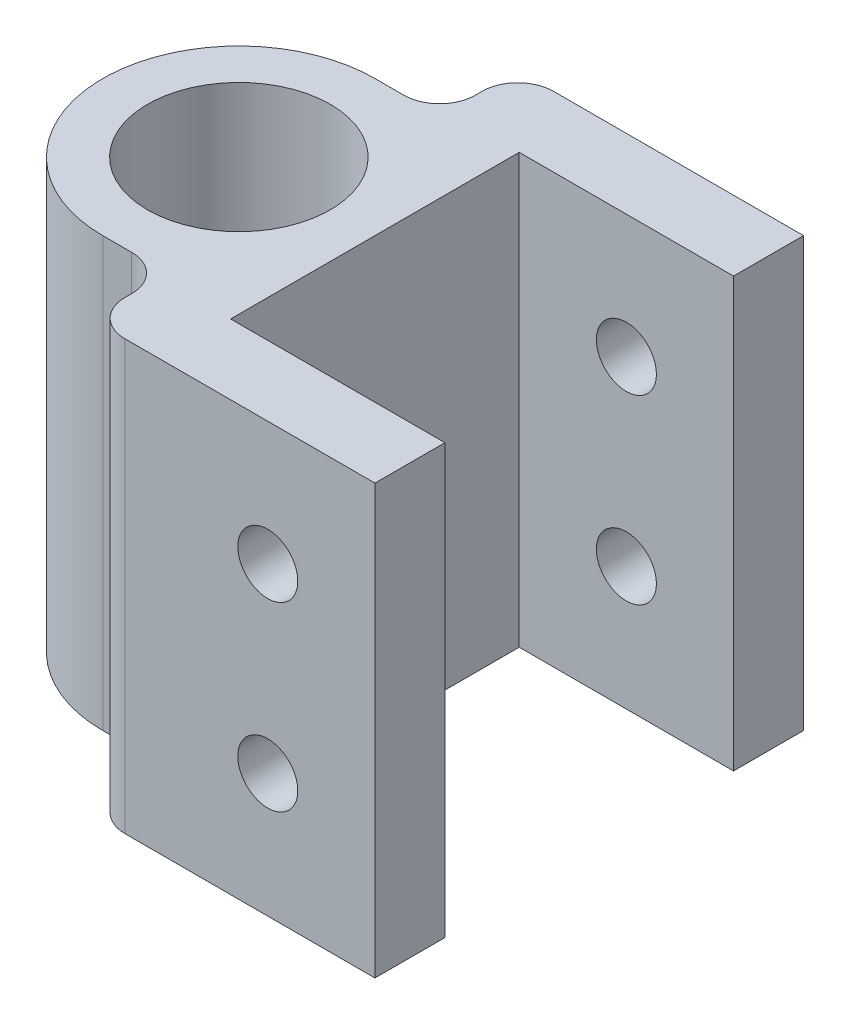
SolidWorks part; units mm, degrees
ref_plane "Front Plane" through (0, 0, 0) normal (0, 0, 1) x (1, 0, 0)
ref_plane "Top Plane" through (0, 0, 0) normal (0, 1, 0) x (1, 0, 0)
ref_plane "Right Plane" through (0, 0, 0) normal (1, 0, 0) x (0, 0, -1)
sketch "Sketch1" plane through (0, 0, 0) normal (0, 1, 0) x (1, 0, 0)
  line L1 (-10.188, 16.8045) -> (-5.188, 16.8045)
  line L2 (-10.188, 16.8045) -> (-10.188, -13.1955)
  line L3 (-10.188, -13.1955) -> (-5.188, -13.1955)
  line L4 (-5.188, 16.8045) -> (-5.188, -13.1955)
  line L5 (-5.188, 16.8045) -> (9.812, 16.8045)
  line L6 (-5.188, 16.8045) -> (-5.188, 11.9045)
  line L7 (-5.188, 11.9045) -> (9.812, 11.9045)
  line L8 (9.812, 16.8045) -> (9.812, 11.9045)
  line L9 (-5.188, -13.1955) -> (9.812, -13.1955)
  line L10 (-5.188, -13.1955) -> (-5.188, -8.2955)
  line L11 (-5.188, -8.2955) -> (9.812, -8.2955)
  line L12 (9.812, -13.1955) -> (9.812, -8.2955)
  line L13 (3.862, -7.7205) -> (-24.238, -7.7205)
  line L14 (3.862, -7.7205) -> (3.862, 11.3295)
  line L15 (3.862, 11.3295) -> (-24.238, 11.3295)
  line L16 (-24.238, -7.7205) -> (-24.238, 11.3295)
  line L17 (3.862, -7.7205) -> (-24.238, 11.3295) construction
  line L18 (3.862, 11.3295) -> (-24.238, -7.7205) construction
  point P10 (-10.188, 1.8045)
  dimension "D1" = 30
  dimension "D2" = 5
  dimension "D3" = 15
  dimension "D4" = 4.9
  dimension "D5" = 4.9
  dimension "D6" = 19.05
  dimension "D7" = 19.05
  dimension "D8" = 15
extrude "Boss-Extrude1" add sketch "Sketch1" along normal blind 30 contours L8 L5 L4 L7 | L15 L4 L1 L2 | L4 L15 L2 L13 | L16 L13 L2 L15 | L4 L13 L2 L3 | L9 L12 L11 L4
sketch "Sketch2" plane through (0, 30, 0) normal (0, 1, 0) x (1, 0, 0)
  line L2 (-5.188, 11.9045) -> (-5.188, -8.2955) construction
  circle A0 centre (-14.713, 1.8045) radius 6.4
  dimension "D1" = 12.8
  dimension "D2" = 9.525
extrude "Cut-Extrude1" cut sketch "Sketch2" against normal through all
sketch "Sketch4" plane through (0, 30, 0) normal (0, 1, 0) x (1, 0, 0)
  line L0 (-5.188, 11.9045) -> (-5.188, -8.2955) construction
  line L1 (-24.238, 11.3295) -> (-5.188, 11.3295)
  line L2 (-24.238, 11.3295) -> (-24.238, -7.7205)
  line L3 (-24.238, -7.7205) -> (-5.188, -7.7205)
  line L4 (-5.188, 11.3295) -> (-5.188, -7.7205)
  line L5 (-10.188, -7.7205) -> (-24.238, -7.7205) construction
  circle A1 centre (-14.713, 1.8045) radius 9.525
  line M7 (-24.238, 11.3295) -> (-24.238, -7.7205)
  dimension "D1" = 0
extrude "Cut-Extrude2" cut sketch "Sketch4" against normal blind 30 contours A1 L1 M7 | A1 L2 L3
fillet "Fillet1" radius 2.5 4 edges at (-10.188, 15, 13.1955) (-10.188, 15, 7.7205) (-10.188, 15, -16.8045) (-10.188, 15, -11.3295)
sketch "Sketch5" plane through (0, 0, -16.8045) normal (0, 0, -1) x (-1, 0, 0)
  line L1 (5.188, 30) -> (-9.812, 30) construction
  line L2 (7.688, 0) -> (-9.812, 0) construction
  circle A0 centre (-2.312, 21.35) radius 1.6007
  circle A1 centre (-2.312, 8.65) radius 1.2868
  point P4 (-2.312, 30)
  dimension "D1" = 0
  dimension "D2" = 12.7
  dimension "D3" = 8.65
  dimension "D4" = 0
hole_wizard "Tap Drill for M5x0.8 Tap1" positions "Sketch6" profile "Sketch7" hole size "M5x0.8" standard "ANSI Metric" end condition through all
sketch "Sketch6" plane through (0, 0, -16.8045) normal (0, 0, -1) x (-1, 0, 0)
  point P0 (-2.312, 21.35)
  point P3 (-2.312, 8.65)
sketch "Sketch7" plane through (2.312, 21.35, -16.8045) normal (1, 0, 0) x (0, 1, 0)
  line L0 (0, 0) -> (0, 30)
  line L1 (0, 30) -> (2.1, 30)
  line L2 (2.1, 30) -> (2.1, 0)
  line L5 (2.1, 0) -> (0, 0)
  line L11 (0, -6.35) -> (0, 107.95) construction
  dimension "Thru Hole Dia." = 4.2
  dimension "Thru Hole Depth" = 30
equation "\"D3@Sketch5\"=(30-12.7)/2"
